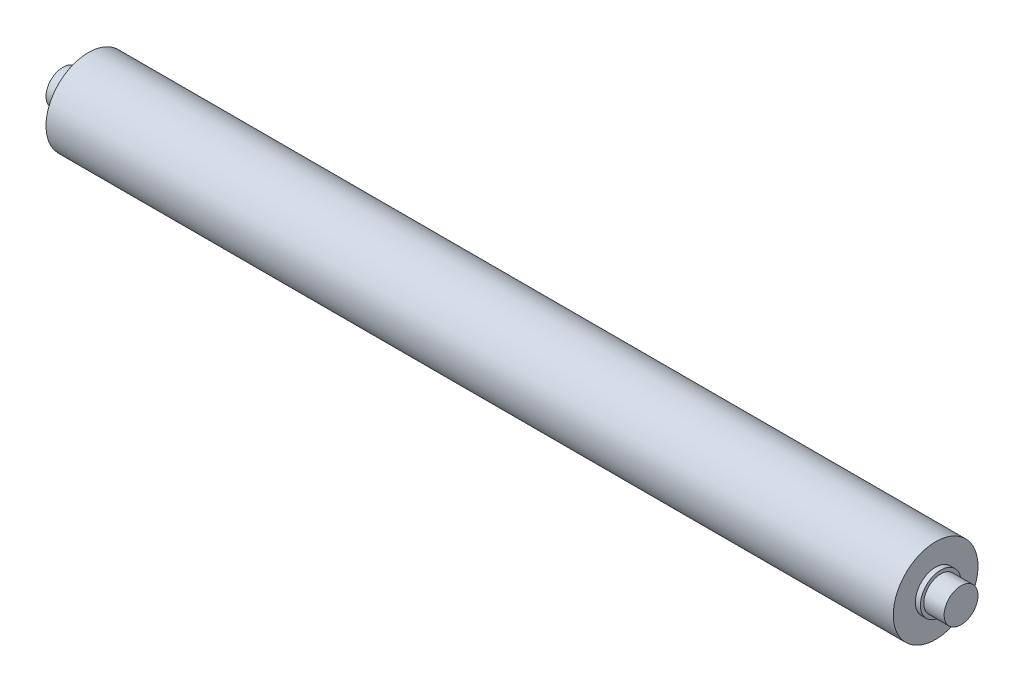
SolidWorks part; units mm, degrees
ref_plane "前视基准面" through (0, 0, 0) normal (0, 0, 1) x (1, 0, 0)
ref_plane "上视基准面" through (0, 0, 0) normal (0, 1, 0) x (1, 0, 0)
ref_plane "右视基准面" through (0, 0, 0) normal (1, 0, 0) x (0, 0, -1)
sketch "草图1" plane through (0, 0, 0) normal (0, 0, 1) x (1, 0, 0)
  line L0 (0, 0) -> (-265, 0) construction
  line L1 (-265, 0) -> (-265, 10)
  line L2 (-265, 10) -> (-253, 10)
  line L3 (-253, 10) -> (-253, 12)
  line L4 (-253, 12) -> (-250, 12)
  line L5 (-250, 12) -> (-250, 25)
  line L6 (-250, 25) -> (250, 25)
  line L7 (265, 0) -> (-265, 0)
  line L8 (247, 22) -> (-247, 22)
  line L9 (-247, 22) -> (-247, 12)
  line L10 (-247, 12) -> (247, 12)
  line L11 (0, 0) -> (0, 24) construction
  line L12 (247, 22) -> (247, 12)
  line L13 (250, 12) -> (250, 25)
  line L14 (253, 12) -> (250, 12)
  line L15 (253, 10) -> (253, 12)
  line L16 (265, 10) -> (253, 10)
  line L17 (265, 0) -> (265, 10)
  point P20 (0, 12)
  dimension "D1" = 12
  dimension "D2" = 3
  dimension "D3" = 2
  dimension "D4" = 500
  dimension "D5" = 12
  dimension "D6" = 20
  dimension "D7" = 3
  dimension "D8" = 50
  dimension "D9" = 3
  dimension "D10" = 12
revolve "旋转1" add sketch "草图1" angle 360 about L7
